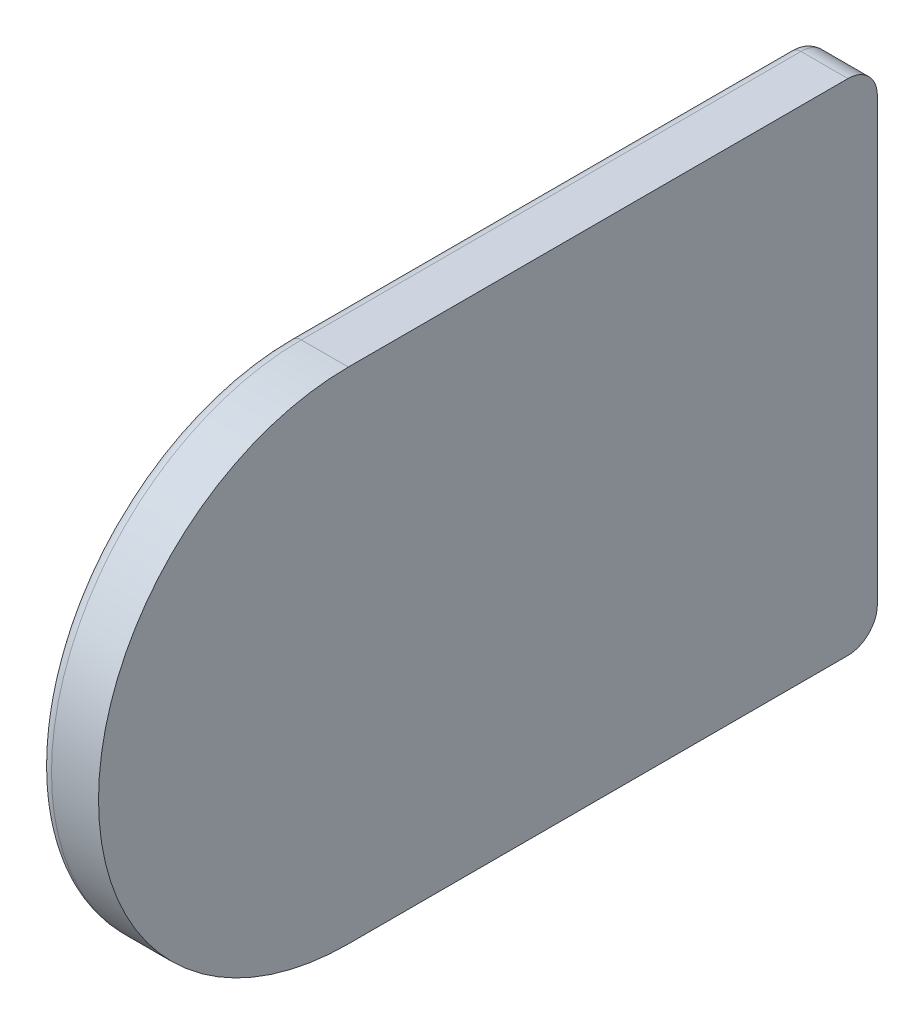
SolidWorks part; units mm, degrees
ref_plane "Front Plane" through (0, 0, 0) normal (0, 0, 1) x (1, 0, 0)
ref_plane "Top Plane" through (0, 0, 0) normal (0, 1, 0) x (1, 0, 0)
ref_plane "Right Plane" through (0, 0, 0) normal (1, 0, 0) x (0, 0, -1)
sketch "Sketch1" plane through (0, 0, 0) normal (1, 0, 0) x (0, 0, -1)
  line L1 (-45, -42.5) -> (40, -42.5)
  line L3 (-45, 42.5) -> (40, 42.5)
  line L4 (45, -37.5) -> (45, 37.5)
  line L5 (-45, -42.5) -> (45, 42.5) construction
  line L6 (-45, 42.5) -> (45, -42.5) construction
  arc A0 (-45, 42.5) -> (-45, -42.5) centre (-45, 0) ccw
  arc A1 (40, -42.5) -> (45, -37.5) centre (40, -37.5) ccw
  arc A2 (40, 42.5) -> (45, 37.5) centre (40, 37.5) cw
  point P0 (0, 0)
  dimension "D3" = 5
  dimension "D1" = 90
  dimension "D2" = 85
extrude "Boss-Extrude1" add sketch "Sketch1" along normal blind 10
fillet "Fillet1" radius 2 6 edges at (0, -42.5, 2.5) (0, -41.0355, -43.5355) (0, 0, -45) (0, 41.0355, -43.5355) (0, 42.5, 2.5) (0, 0, 87.5)
sketch "Sketch2" plane through (0, 0, 0) normal (-1, 0, 0) x (0, 0, 1)
  line L0 (0, 0) -> (-43, 0) construction
  line L6 (2, 13.75) -> (23, 13.75)
  line L7 (-43, 37.5) -> (-43, -37.5) construction
  line L8 (2, 13.75) -> (2, 16.25)
  line L9 (2, 16.25) -> (23, 16.25)
  line L10 (23, 13.75) -> (23, 16.25)
  dimension "D1" = 16.25
  dimension "D2" = 21
  dimension "D3" = 2.5
  dimension "D4" = 45
extrude "Boss-Extrude2" add sketch "Sketch2" along normal blind 20
mirror "Mirror1" about plane through (0, 0, 0) normal (0, 1, 0) of "Boss-Extrude2"
sketch "Sketch3" plane through (0, 16.25, 0) normal (0, 1, 0) x (1, 0, 0)
  line L0 (-20, -23) -> (-20, -2) construction
  circle A0 centre (-13, -12.5) radius 2.25
  point P4 (-20, -12.5)
  dimension "D1" = 4.5
  dimension "D2" = 7
extrude "Cut-Extrude1" cut sketch "Sketch3" against normal through all
